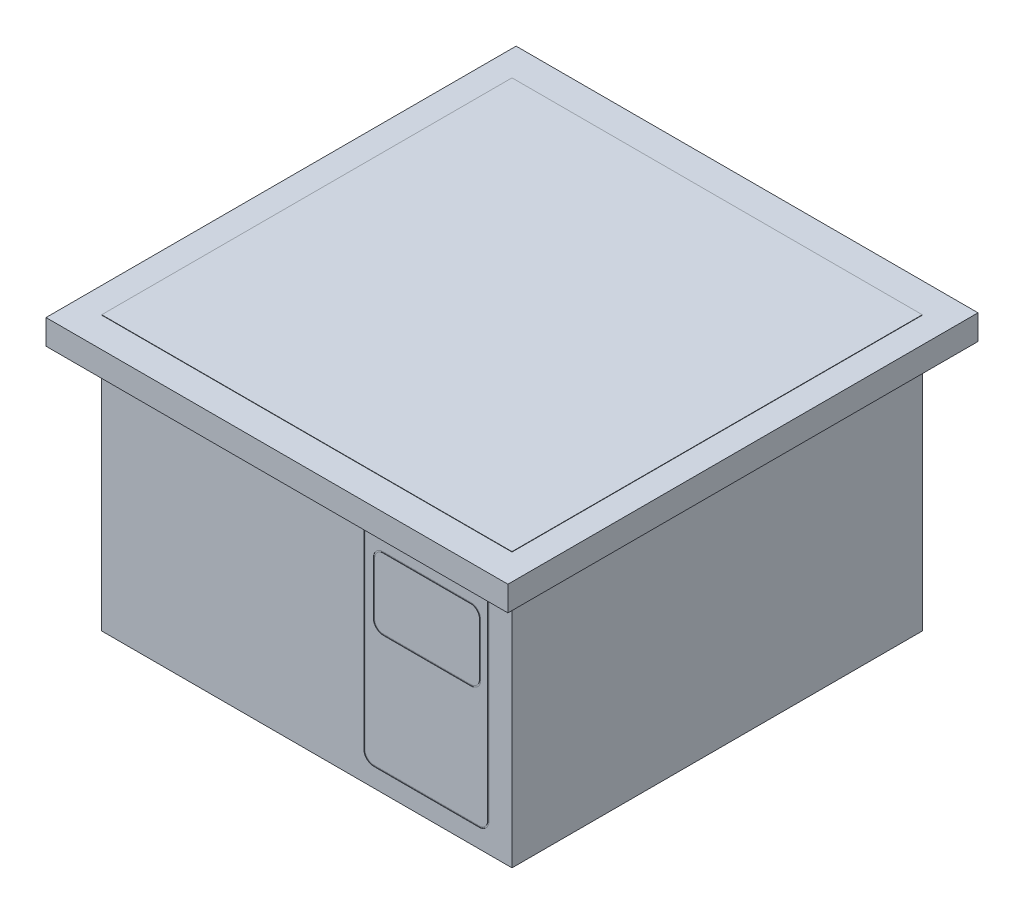
SolidWorks part; units mm, degrees
ref_plane "Alzado" through (0, 0, 0) normal (0, 0, 1) x (1, 0, 0)
ref_plane "Planta" through (0, 0, 0) normal (0, 1, 0) x (1, 0, 0)
ref_plane "Vista lateral" through (0, 0, 0) normal (1, 0, 0) x (0, 0, -1)
sketch "Croquis1" plane through (0, 0, 0) normal (0, 1, 0) x (1, 0, 0)
  line L0 (-1500, 1500) -> (-1500, -1500)
  line L1 (-1650, 1650) -> (1650, 1650)
  line L2 (-1650, 1650) -> (-1650, -1650)
  line L3 (-1650, -1650) -> (1650, -1650)
  line L4 (1650, 1650) -> (1650, -1650)
  line L5 (-1650, 1650) -> (1650, -1650) construction
  line L6 (-1650, -1650) -> (1650, 1650) construction
  line L7 (-1500, -1500) -> (1500, -1500)
  line L8 (1500, 1500) -> (1500, -1500)
  line L9 (-1500, 1500) -> (1500, 1500)
  point P0 (0, 0)
  dimension "D1" = 3300
  dimension "D2" = 3300
  dimension "D3" = 150
extrude "Saliente-Extruir1" add sketch "Croquis1" along normal blind 2000
sketch "Croquis2" plane through (0, 2000, 0) normal (0, 1, 0) x (1, 0, 0)
  line L1 (-1857.5539, -1890.4617) -> (1857.5539, -1890.4617)
  line L2 (-1857.5539, -1890.4617) -> (-1857.5539, 1890.4617)
  line L3 (-1857.5539, 1890.4617) -> (1857.5539, 1890.4617)
  line L4 (1857.5539, -1890.4617) -> (1857.5539, 1890.4617)
  line L5 (-1857.5539, -1890.4617) -> (1857.5539, 1890.4617) construction
  line L6 (-1857.5539, 1890.4617) -> (1857.5539, -1890.4617) construction
  line L7 (-1650, 1650) -> (1650, 1650)
  line L8 (-1650, 1650) -> (-1650, -1650)
  line L9 (-1650, -1650) -> (1650, -1650)
  line L10 (1650, 1650) -> (1650, -1650)
  line L11 (-1650, 1650) -> (1650, -1650) construction
  line L12 (-1650, -1650) -> (1650, 1650) construction
  point P0 (0, 0)
  point P6 (0, 0)
extrude "Saliente-Extruir2" add sketch "Croquis2" along normal blind 200 separate body
sketch "Croquis3" plane through (0, 0, 1650) normal (0, 0, 1) x (1, 0, 0)
  line L0 (458.6934, 1745.1353) -> (458.6934, 231.1014)
  line L1 (538.6934, 1815.1353) -> (1384.4613, 1815.1353)
  line L2 (468.6934, 1745.1353) -> (468.6934, 231.1014)
  line L3 (538.6934, 161.1014) -> (1384.4613, 161.1014)
  line L4 (1454.4613, 1745.1353) -> (1454.4613, 231.1014)
  line L5 (468.6934, 1815.1353) -> (1454.4613, 161.1014) construction
  line L6 (468.6934, 161.1014) -> (1454.4613, 1815.1353) construction
  line L7 (538.6934, 151.1014) -> (1384.4613, 151.1014)
  line L8 (1464.4613, 1745.1353) -> (1464.4613, 231.1014)
  line L9 (538.6934, 1825.1353) -> (1384.4613, 1825.1353)
  arc A0 (468.6934, 231.1014) -> (538.6934, 161.1014) centre (538.6934, 231.1014) ccw
  arc A1 (1384.4613, 161.1014) -> (1454.4613, 231.1014) centre (1384.4613, 231.1014) ccw
  arc A2 (1384.4613, 1815.1353) -> (1454.4613, 1745.1353) centre (1384.4613, 1745.1353) cw
  arc A3 (538.6934, 1815.1353) -> (468.6934, 1745.1353) centre (538.6934, 1745.1353) ccw
  arc A4 (458.6934, 231.1014) -> (538.6934, 151.1014) centre (538.6934, 231.1014) ccw
  arc A5 (1384.4613, 151.1014) -> (1464.4613, 231.1014) centre (1384.4613, 231.1014) ccw
  arc A6 (1384.4613, 1825.1353) -> (1464.4613, 1745.1353) centre (1384.4613, 1745.1353) cw
  arc A7 (538.6934, 1825.1353) -> (458.6934, 1745.1353) centre (538.6934, 1745.1353) ccw
  point P0 (961.5773, 988.1184)
  dimension "D1" = 70
  dimension "D2" = 10
extrude "Cortar-Extruir1" cut sketch "Croquis3" against normal blind 3
sketch "Croquis4" plane through (0, 0, 1650) normal (0, 0, 1) x (1, 0, 0)
  line L0 (535.2428, 1604.1703) -> (535.2428, 1181.9157)
  line L1 (615.2428, 1674.1703) -> (1318.6248, 1674.1703)
  line L2 (545.2428, 1604.1703) -> (545.2428, 1181.9157)
  line L3 (615.2428, 1111.9157) -> (1318.6248, 1111.9157)
  line L4 (1388.6248, 1604.1703) -> (1388.6248, 1181.9157)
  line L5 (545.2428, 1674.1703) -> (1388.6248, 1111.9157) construction
  line L6 (545.2428, 1111.9157) -> (1388.6248, 1674.1703) construction
  line L7 (615.2428, 1101.9157) -> (1318.6248, 1101.9157)
  line L8 (1398.6248, 1604.1703) -> (1398.6248, 1181.9157)
  line L9 (615.2428, 1684.1703) -> (1318.6248, 1684.1703)
  arc A0 (545.2428, 1181.9157) -> (615.2428, 1111.9157) centre (615.2428, 1181.9157) ccw
  arc A1 (1318.6248, 1111.9157) -> (1388.6248, 1181.9157) centre (1318.6248, 1181.9157) ccw
  arc A2 (1318.6248, 1674.1703) -> (1388.6248, 1604.1703) centre (1318.6248, 1604.1703) cw
  arc A3 (615.2428, 1674.1703) -> (545.2428, 1604.1703) centre (615.2428, 1604.1703) ccw
  arc A4 (535.2428, 1181.9157) -> (615.2428, 1101.9157) centre (615.2428, 1181.9157) ccw
  arc A5 (1318.6248, 1101.9157) -> (1398.6248, 1181.9157) centre (1318.6248, 1181.9157) ccw
  arc A6 (1318.6248, 1684.1703) -> (1398.6248, 1604.1703) centre (1318.6248, 1604.1703) cw
  arc A7 (615.2428, 1684.1703) -> (535.2428, 1604.1703) centre (615.2428, 1604.1703) ccw
  point P0 (966.9338, 1393.043)
  dimension "D1" = 70
  dimension "D2" = 10
extrude "Cortar-Extruir2" cut sketch "Croquis4" against normal blind 3
sketch "Croquis5" plane through (0, 2200, 0) normal (0, 1, 0) x (1, 0, 0)
  line L1 (-1650, 1650) -> (1650, 1650)
  line L2 (-1650, 1650) -> (-1650, -1650)
  line L3 (-1650, -1650) -> (1650, -1650)
  line L4 (1650, 1650) -> (1650, -1650)
  line L5 (-1650, 1650) -> (1650, -1650) construction
  line L6 (-1650, -1650) -> (1650, 1650) construction
  point P0 (0, 0)
extrude "Saliente-Extruir3" add sketch "Croquis5" along normal blind 3 separate body
